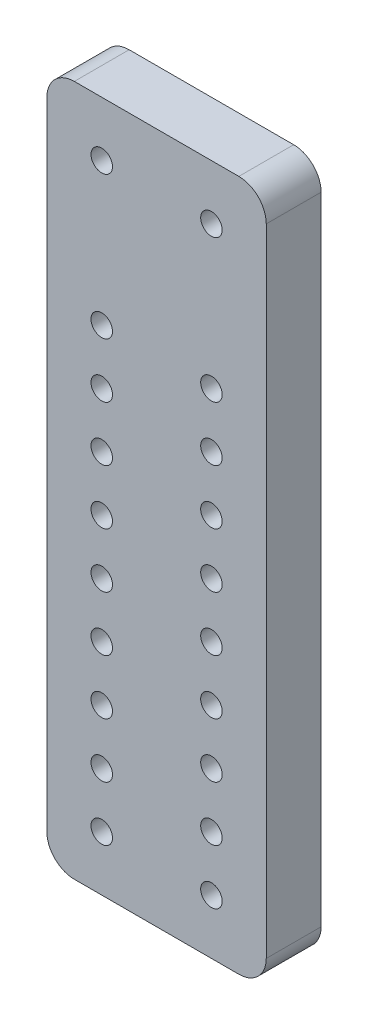
SolidWorks part; units mm, degrees
material "PET"
ref_plane "Front Plane" through (0, 0, 0) normal (0, 0, 1) x (1, 0, 0)
ref_plane "Top Plane" through (0, 0, 0) normal (0, 1, 0) x (1, 0, 0)
ref_plane "Right Plane" through (0, 0, 0) normal (1, 0, 0) x (0, 0, -1)
sketch "Sketch2" plane through (0, 0, 0) normal (0, 0, 1) x (1, 0, 0)
  line L1 (0, 0) -> (50.8, 0)
  line L2 (0, 0) -> (0, 160.02)
  line L3 (0, 160.02) -> (50.8, 160.02)
  line L4 (50.8, 0) -> (50.8, 160.02)
  dimension "D1" = 50.8
  dimension "D2" = 160.02
extrude "Boss-Extrude1" add sketch "Sketch2" against normal blind 12.7
sketch "Sketch3" plane through (0, 0, 0) normal (0, 0, 1) x (1, 0, 0)
  line L0 (50.8, 160.02) -> (0, 160.02) construction
  line L1 (0, 160.02) -> (0, 0) construction
  circle A0 centre (12.7, 147.32) radius 2.4892
  circle A17 centre (38.1, 147.32) radius 2.4892
  circle A24 centre (12.7, 114.3) radius 2.4892
  circle A25 centre (12.7, 101.6) radius 2.4892
  circle A26 centre (12.7, 88.9) radius 2.4892
  circle A27 centre (12.7, 76.2) radius 2.4892
  circle A28 centre (12.7, 63.5) radius 2.4892
  circle A29 centre (12.7, 50.8) radius 2.4892
  circle A30 centre (12.7, 38.1) radius 2.4892
  circle A31 centre (12.7, 25.4) radius 2.4892
  circle A32 centre (12.7, 12.7) radius 2.4892
  circle A33 centre (38.1, 101.6) radius 2.4892
  circle A34 centre (38.1, 88.9) radius 2.4892
  circle A35 centre (38.1, 76.2) radius 2.4892
  circle A36 centre (38.1, 63.5) radius 2.4892
  circle A37 centre (38.1, 50.8) radius 2.4892
  circle A38 centre (38.1, 38.1) radius 2.4892
  circle A39 centre (38.1, 25.4) radius 2.4892
  circle A40 centre (38.1, 12.7) radius 2.4892
  circle A41 centre (38.1, 114.3) radius 2.4892
  dimension "D1" = 4.9784
  dimension "D6" = 4.9784
  dimension "D2" = 12.7
  dimension "D3" = 12.7
  dimension "D7" = 12.7
  dimension "D8" = 33.02
  dimension "D4" = 1
  dimension "D5" = 2
  dimension "D9" = 9
  dimension "D10" = 2
extrude "Cut-Extrude1" cut sketch "Sketch3" against normal through all
fillet "Fillet1" radius 6.35 4 edges at (0, 0, -6.35) (50.8, 0, -6.35) (50.8, 160.02, -6.35) (0, 160.02, -6.35)
